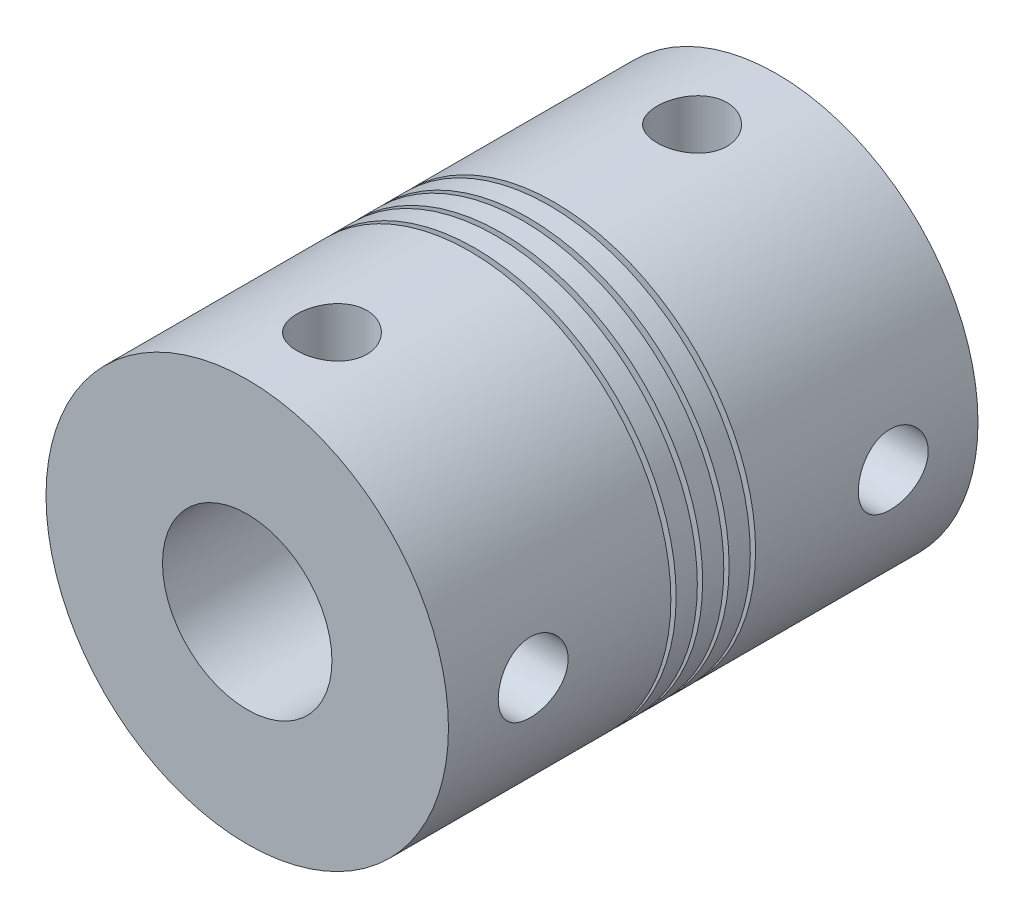
SolidWorks part; units mm, degrees
ref_plane "Front Plane" through (0, 0, 0) normal (0, 0, 1) x (1, 0, 0)
ref_plane "Top Plane" through (0, 0, 0) normal (0, 1, 0) x (1, 0, 0)
ref_plane "Right Plane" through (0, 0, 0) normal (1, 0, 0) x (0, 0, -1)
sketch "Sketch1" plane through (0, 0, 0) normal (0, 1, 0) x (1, 0, 0)
  line L0 (0, 0) -> (72.3335, 0) construction
  line L1 (0, 0) -> (0, 87.4347) construction
  line L2 (4, 0) -> (9.5, 0)
  line L3 (9.5, 0) -> (9.5, 10.5)
  line L4 (9.5, 10.5) -> (9, 10.5)
  line L5 (9, 10.5) -> (9, 10.75)
  line L6 (9, 10.75) -> (9.5, 10.75)
  line L7 (9.5, 10.75) -> (9.5, 11.75)
  line L8 (9.5, 11.75) -> (9, 11.75)
  line L9 (9, 11.75) -> (9, 12)
  line L10 (9, 12) -> (9.5, 12)
  line L11 (9.5, 12) -> (9.5, 13)
  line L12 (9.5, 13) -> (9, 13)
  line L13 (9, 13) -> (9, 13.25)
  line L14 (9, 13.25) -> (9.5, 13.25)
  line L15 (9.5, 13.25) -> (9.5, 14.25)
  line L16 (9.5, 14.25) -> (9, 14.25)
  line L17 (9, 14.25) -> (9, 14.5)
  line L18 (9, 14.5) -> (9.5, 14.5)
  line L19 (9.5, 14.5) -> (9.5, 25)
  line L20 (9.5, 25) -> (4, 25)
  line L21 (4, 25) -> (4, 0)
  line L22 (0, 12.5) -> (19.1193, 12.5) construction
  dimension "D1" = 4
  dimension "D2" = 9.5
  dimension "D3" = 9.5
  dimension "D4" = 25
  dimension "D5" = 0.5
  dimension "D6" = 0.5
  dimension "D7" = 0.5
  dimension "D8" = 0.5
  dimension "D9" = 0.25
  dimension "D10" = 0.25
  dimension "D11" = 0.25
  dimension "D12" = 0.25
  dimension "D13" = 1
  dimension "D14" = 1
  dimension "D15" = 1
  dimension "D16" = 0.5
  dimension "D17" = 12.5
  dimension "D18" = 0.5
  dimension "D19" = 0.5
  dimension "D20" = 0.5
revolve "Revolve3" add sketch "Sketch1" angle 360 about L1
sketch "Sketch2" plane through (0, 0, 0) normal (0, 1, 0) x (1, 0, 0)
  line L0 (0, 0) -> (0, 25.4801) construction
  line L1 (9.5, 25) -> (-9.5, 25) construction
  point P3 (0, 4)
  point P4 (0, 21)
  point P7 (0, 4)
  dimension "D1" = 4
  dimension "D2" = 4
hole_wizard "M4x0.7 Tapped Hole1" positions "Sketch2" profile "Sketch3" tap size "M4x0.7" standard "ANSI Metric"
sketch "Sketch3" plane through (0, 0, -4) normal (1, 0, 0) x (0, 0, -1)
  line L0 (0, 0) -> (0, 11.0914)
  line L1 (0, 11.0914) -> (1.65, 10.1)
  line L2 (1.65, 10.1) -> (1.65, 0)
  line L5 (1.65, 0) -> (0, 0)
  line L10 (0, 11.0914) -> (-1.65, 10.1) construction
  line L11 (0, -6.35) -> (0, 107.95) construction
  dimension "Tap Drill Dia." = 3.3
  dimension "Tap Drill Depth" = 10.1
  dimension "Drill Angle" = 118
cosmetic thread "Hole Thread1" parameters "D1"=8, "D2"=4
cosmetic thread "Hole Thread2" parameters "D1"=8, "D2"=4
cosmetic thread "Hole Thread3" parameters "D1"=8, "D2"=4
sketch "Sketch6" plane through (0, 0, 0) normal (1, 0, 0) x (0, 0, -1)
  line L0 (-0.7472, 0) -> (27.135, 0) construction
  line L1 (25, -9.5) -> (25, 9.5) construction
  point P3 (4, 0)
  point P4 (21, 0)
  point P7 (21, 0)
  point P9 (4, 0)
  point P11 (4, 0)
  dimension "D1" = 4
  dimension "D2" = 4
hole_wizard "M4x0.7 Tapped Hole2" positions "Sketch6" profile "Sketch7" tap size "M4x0.7" standard "ANSI Metric"
sketch "Sketch7" plane through (0, 0, -4) normal (0, 1, 0) x (0, 0, 1)
  line L0 (0, 0) -> (0, 11.0914)
  line L1 (0, 11.0914) -> (1.65, 10.1)
  line L2 (1.65, 10.1) -> (1.65, 0)
  line L5 (1.65, 0) -> (0, 0)
  line L10 (0, 11.0914) -> (-1.65, 10.1) construction
  line L11 (0, -6.35) -> (0, 107.95) construction
  dimension "Tap Drill Dia." = 3.3
  dimension "Tap Drill Depth" = 10.1
  dimension "Drill Angle" = 118
cosmetic thread "Hole Thread4" parameters "D1"=8, "D2"=4
cosmetic thread "Hole Thread5" parameters "D1"=8, "D2"=4
cosmetic thread "Hole Thread6" parameters "D1"=8, "D2"=4
cosmetic thread "Hole Thread7" parameters "D1"=8, "D2"=4
cosmetic thread "Hole Thread8" parameters "D1"=8, "D2"=4
